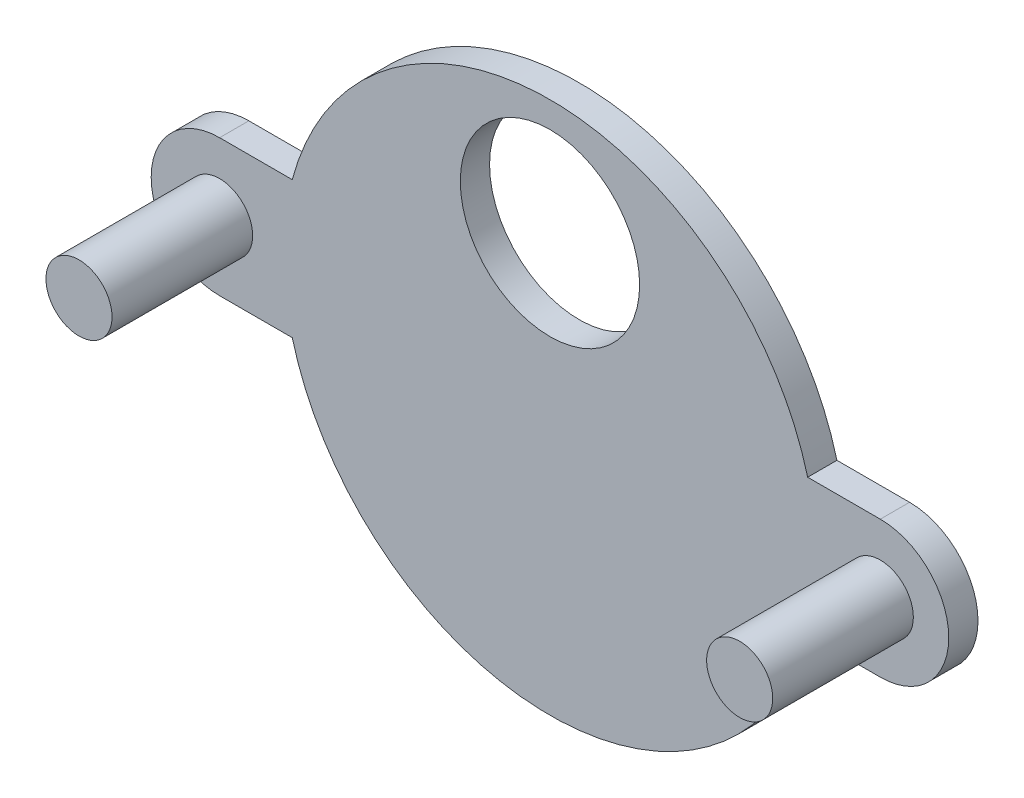
SolidWorks part; units mm, degrees
ref_plane "Front Plane" through (0, 0, 0) normal (0, 0, 1) x (1, 0, 0)
ref_plane "Top Plane" through (0, 0, 0) normal (0, 1, 0) x (1, 0, 0)
ref_plane "Right Plane" through (0, 0, 0) normal (1, 0, 0) x (0, 0, -1)
sketch "Sketch1" plane through (0, 0, 0) normal (0, 0, 1) x (1, 0, 0)
  circle A3 centre (0, 0) radius 14.125
  point P3 (0, 0)
  dimension "D1" = 28.25
extrude "Boss-Extrude1" add sketch "Sketch1" along normal blind 1.55
sketch "Sketch2" plane through (0, 0, 0) normal (0, 0, 1) x (1, 0, 0)
  line L0 (-17.5, 0) -> (17.5, 0) construction
  line L1 (-17.5, 3.625) -> (17.5, 3.625)
  line L2 (-17.5, -3.625) -> (17.5, -3.625)
  arc A0 (-17.5, 3.625) -> (-17.5, -3.625) centre (-17.5, 0) ccw
  arc A1 (17.5, -3.625) -> (17.5, 3.625) centre (17.5, 0) ccw
  point P4 (0, 0)
  point P9 (0, 0)
  point P10 (0, 0)
  dimension "D2" = 3.625
  dimension "D1" = 35
extrude "Boss-Extrude2" add sketch "Sketch2" along normal up to surface (1.55 mm away) up to face at (14.125, 0, 1.55)
sketch "Sketch4" plane through (0, 0, 0) normal (0, 0, 1) x (1, 0, 0)
  circle A2 centre (-17.5, 0) radius 1.75
  circle A3 centre (17.5, 0) radius 1.75
  point P2 (0, 0)
  point P5 (0, 0)
  point P6 (0, 0)
  dimension "D1" = 3.5
  dimension "D2" = 17.5
  dimension "D3" = 3.5
  dimension "D4" = 17.5
extrude "Boss-Extrude3" add sketch "Sketch4" along normal blind 9
sketch "Sketch5" plane through (0, 0, 0) normal (0, 0, -1) x (-1, 0, 0)
  circle A2 centre (0, 8) radius 4.75
  point P0 (0, 0)
  dimension "D1" = 9.5
extrude "Cut-Extrude1" cut sketch "Sketch5" against normal up to next
